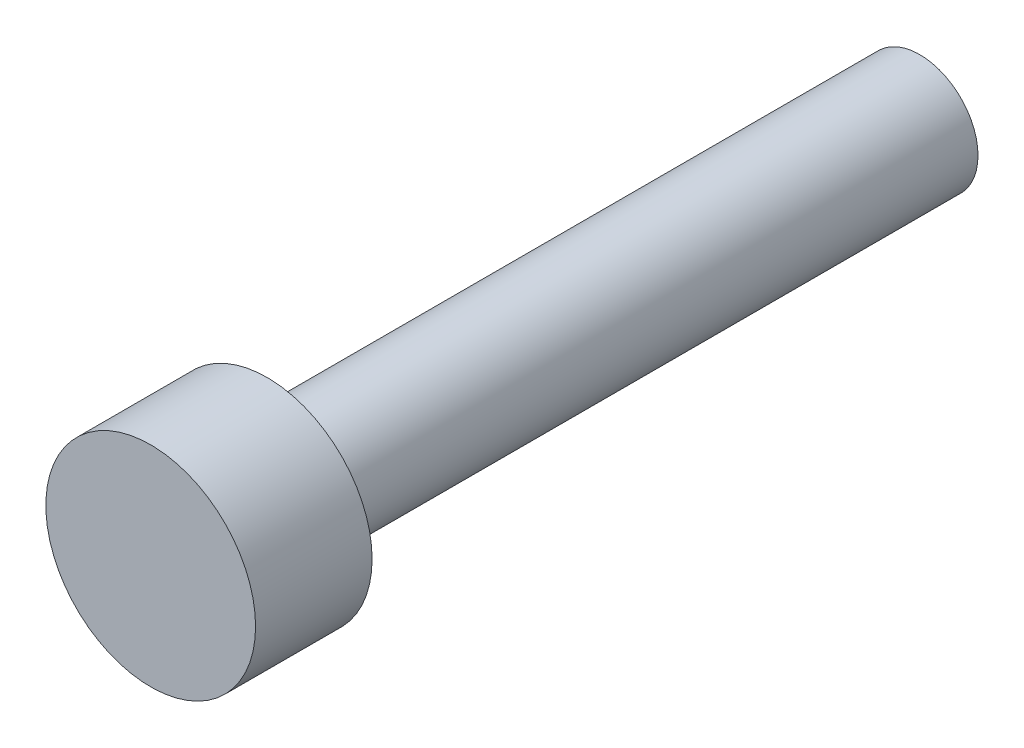
SolidWorks part; units mm, degrees
ref_plane "Front Plane" through (0, 0, 0) normal (0, 0, 1) x (1, 0, 0)
ref_plane "Top Plane" through (0, 0, 0) normal (0, 1, 0) x (1, 0, 0)
ref_plane "Right Plane" through (0, 0, 0) normal (1, 0, 0) x (0, 0, -1)
sketch "Shank_nominal_thread_envelope_profile" plane through (0, 0, 0) normal (0, 0, 1) x (1, 0, 0)
  circle A0 centre (0, 0) radius 1.25
  dimension "D1" = 2.5
extrude "Shank_nominal_thread_envelope" add sketch "Shank_nominal_thread_envelope_profile" along normal blind 14 from offset 14
sketch "Socket_head_envelope_profile" plane through (0, 0, 0) normal (0, 0, 1) x (1, 0, 0)
  circle A0 centre (0, 0) radius 2.25
  dimension "D1" = 4.5
extrude "Socket_head_envelope" add sketch "Socket_head_envelope_profile" along normal blind 2.5
